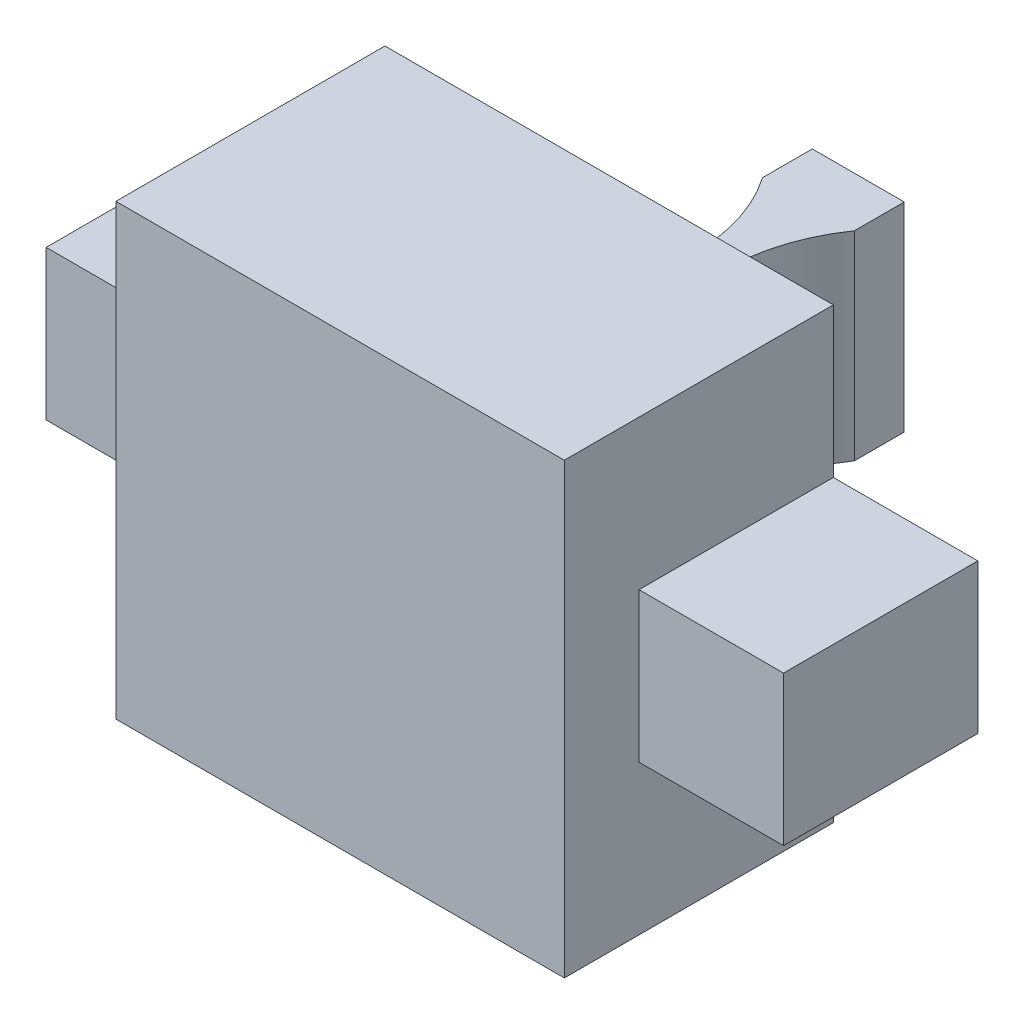
SolidWorks part; units mm, degrees
ref_plane "정면" through (0, 0, 0) normal (0, 0, 1) x (1, 0, 0)
ref_plane "윗면" through (0, 0, 0) normal (0, 1, 0) x (1, 0, 0)
ref_plane "우측면" through (0, 0, 0) normal (1, 0, 0) x (0, 0, -1)
sketch "스케치1" plane through (0, 0, 0) normal (0, 0, 1) x (1, 0, 0)
  line L1 (0, 0) -> (9, 0)
  line L2 (0, 0) -> (0, 9)
  line L3 (0, 9) -> (9, 9)
  line L4 (9, 0) -> (9, 9)
  dimension "D1" = 9
  dimension "D2" = 9
extrude "보스-돌출1" add sketch "스케치1" along normal blind 5.4
sketch "스케치2" plane through (0, 0, 0) normal (0, 0, -1) x (-1, 0, 0)
  line L0 (0, 9) -> (0, 0) construction
  line L1 (0, 6) -> (2.9, 6)
  line L2 (0, 6) -> (0, 3)
  line L3 (0, 3) -> (2.9, 3)
  line L4 (2.9, 6) -> (2.9, 3)
  line L5 (-4.5, 9) -> (-4.5, 2.1107) construction
  line L7 (-9, 9) -> (0, 9) construction
  line L8 (-11.9, 6) -> (-11.9, 3)
  line L9 (-9, 3) -> (-11.9, 3)
  line L10 (-9, 6) -> (-9, 3)
  line L11 (-9, 6) -> (-11.9, 6)
  point P9 (-4.5, 9)
  point P11 (0, 0)
  point P12 (0, 4.5)
  point P13 (0, 4.5)
  point P18 (-9, 4.5)
  dimension "D1" = 2.9
  dimension "D2" = 3
extrude "보스-돌출2" add sketch "스케치2" against normal blind 3.9
ref_plane "평면1" through (0, 4.5, 0) normal (0, 1, 0) x (1, 0, 0)
sketch "스케치3" plane through (0, 4.5, 0) normal (0, 1, 0) x (1, 0, 0)
  line L0 (9, 0) -> (0, 0) construction
  line L1 (3.5778, 4) -> (3.5778, 5)
  line L2 (3.5778, 5) -> (5.4222, 5)
  line L3 (3.5778, 0) -> (5.4222, 0)
  line L4 (4.5, 6) -> (4.5, -5.9536) construction
  line L5 (5.4222, 4) -> (5.4222, 5)
  arc A0 (3.5778, 0) -> (3.5778, 4) centre (0.7055, 2) ccw
  arc A1 (5.4222, 0) -> (5.4222, 4) centre (8.2945, 2) cw
  point P4 (4.5, 0)
  point P14 (4.5, 0)
  point P17 (4.5, 5)
  dimension "D1" = 3.5
  dimension "D2" = 4
  dimension "D3" = 1
  dimension "D4" = 0.7055
extrude "보스-돌출3" add sketch "스케치3" along normal mid plane 4
